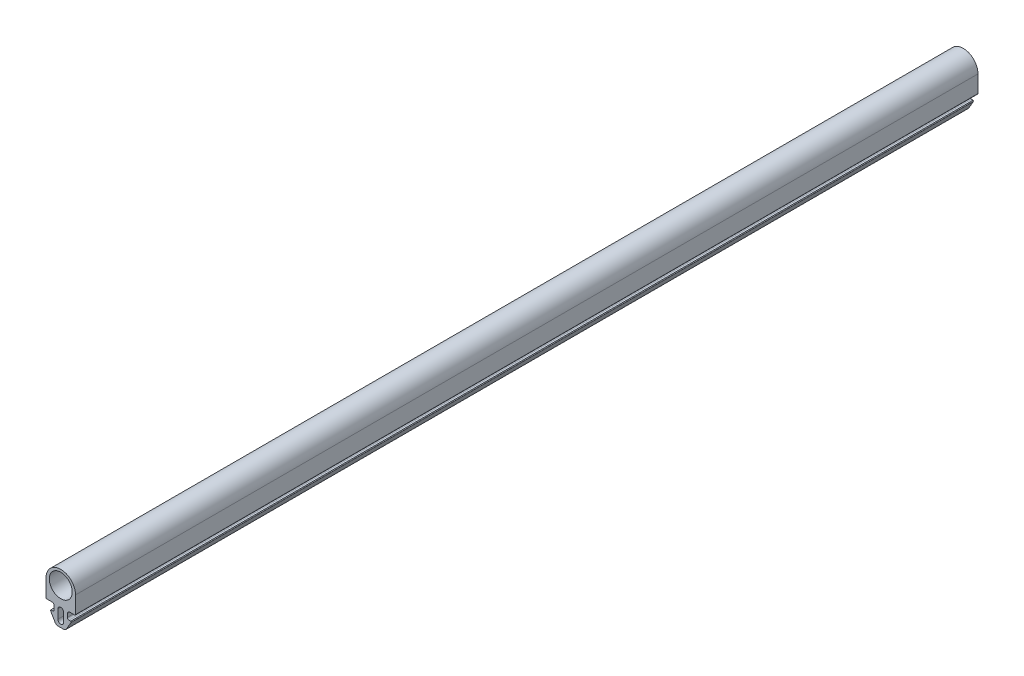
SolidWorks part; units mm, degrees
ref_plane "Plan de face" through (0, 0, 0) normal (0, 0, 1) x (1, 0, 0)
ref_plane "Plan de dessus" through (0, 0, 0) normal (0, 1, 0) x (1, 0, 0)
ref_plane "Plan de droite" through (0, 0, 0) normal (1, 0, 0) x (0, 0, -1)
ref_plane "Plan1" through (0, 0, 20) normal (0, 0, 1) x (1, 0, 0)
sketch "Esquisse1" plane through (0, 0, 20) normal (0, 0, 1) x (1, 0, 0)
  line L0 (-9, 10.8646) -> (-9, 0.5239)
  line L1 (-8.4781, 0) -> (-5.5, 0)
  line L2 (-4, -1.5) -> (-4, -3.5)
  line L3 (-5, -4.5) -> (-6.016, -4.5)
  line L4 (-6.1742, -5.1677) -> (-3.44, -9.9034)
  line L5 (-1.708, -10.9034) -> (1.708, -10.9034)
  line L6 (3.44, -9.9034) -> (6.1742, -5.1677)
  line L7 (6.016, -4.5) -> (5, -4.5)
  line L8 (4, -3.5) -> (4, -1.5)
  line L9 (5.5, 0) -> (8.4781, 0)
  line L10 (9, 0.5239) -> (9, 10.8646)
  line L11 (1.75, -1.9534) -> (1.75, -7.3515)
  line L12 (-1.75, -7.3515) -> (-1.75, -1.9534)
  arc A0 (9, 10.8646) -> (-9, 10.8646) centre (0, 10.8646) ccw
  arc A1 (-9, 0.5239) -> (-8.4781, 0) centre (-8.5006, 0.4995) ccw
  arc A2 (-5.5, 0) -> (-4, -1.5) centre (-5.5, -1.5) cw
  arc A3 (-4, -3.5) -> (-5, -4.5) centre (-5, -3.5) cw
  arc A4 (-6.016, -4.5) -> (-6.1742, -5.1677) centre (-5.7412, -4.9177) ccw
  arc A5 (-3.44, -9.9034) -> (-1.708, -10.9034) centre (-1.708, -8.9034) ccw
  arc A6 (1.708, -10.9034) -> (3.44, -9.9034) centre (1.708, -8.9034) ccw
  arc A7 (6.1742, -5.1677) -> (6.016, -4.5) centre (5.7412, -4.9177) ccw
  arc A8 (5, -4.5) -> (4, -3.5) centre (5, -3.5) cw
  arc A9 (4, -1.5) -> (5.5, 0) centre (5.5, -1.5) cw
  arc A10 (8.4781, 0) -> (9, 0.5239) centre (8.5006, 0.4995) ccw
  arc A11 (-1.75, -1.9534) -> (1.75, -1.9534) centre (0, -1.9534) cw
  arc A12 (1.75, -7.3515) -> (-1.75, -7.3515) centre (0, -7.3515) cw
  circle A13 centre (0, 11.36) radius 7
extrude "Boss.-Extru.1" add sketch "Esquisse1" against normal blind 550
